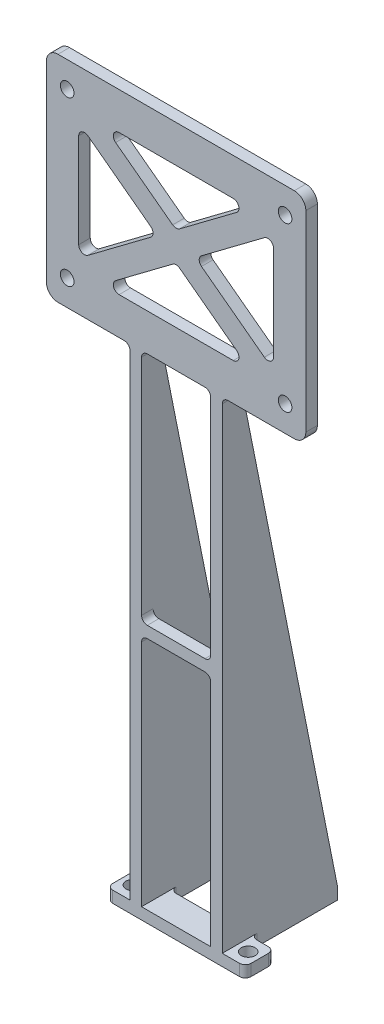
SolidWorks part; units mm, degrees
material "7075-T6 (SN)"
ref_plane "Front Plane" through (0, 0, 0) normal (0, 0, 1) x (1, 0, 0)
ref_plane "Top Plane" through (0, 0, 0) normal (0, 1, 0) x (1, 0, 0)
ref_plane "Right Plane" through (0, 0, 0) normal (1, 0, 0) x (0, 0, -1)
sketch "Sketch1" plane through (0, 0, 0) normal (0, 0, 1) x (-1, 0, 0)
  line L8 (-27.9, -31.869) -> (27.9, -31.869)
  line L9 (31.869, -27.9) -> (31.869, 27.9)
  line L10 (27.9, 31.869) -> (-27.9, 31.869)
  line L11 (-31.869, 27.9) -> (-31.869, -27.9)
  arc A2 (-25.5, 18) -> (-22.5, 18) centre (-24, 18) ccw
  arc A3 (-22.5, 18) -> (-25.5, 18) centre (-24, 18) ccw
  arc A8 (27.9, -31.869) -> (31.869, -27.9) centre (27.9, -27.9) ccw
  arc A9 (31.869, 27.9) -> (27.9, 31.869) centre (27.9, 27.9) ccw
  arc A10 (-27.9, 31.869) -> (-31.869, 27.9) centre (-27.9, 27.9) ccw
  arc A11 (-31.869, -27.9) -> (-27.9, -31.869) centre (-27.9, -27.9) ccw
  arc A14 (22.5, 18) -> (25.5, 18) centre (24, 18) ccw
  arc A15 (25.5, 18) -> (22.5, 18) centre (24, 18) ccw
  arc A18 (25.5, -18) -> (22.5, -18) centre (24, -18) ccw
  arc A19 (22.5, -18) -> (25.5, -18) centre (24, -18) ccw
  arc A22 (-22.5, -18) -> (-25.5, -18) centre (-24, -18) ccw
  arc A23 (-25.5, -18) -> (-22.5, -18) centre (-24, -18) ccw
extrude "Boss-Extrude1" add sketch "Sketch1" along normal blind 2.54
sketch "Sketch2" plane through (0, 0, 2.54) normal (0, 0, 1) x (1, 0, 0)
  line L0 (-24, 18) -> (-24, -18) construction
  line L1 (-24, -18) -> (24, -18) construction
  line L3 (-24, 18) -> (24, 18) construction
  line L4 (24, -18) -> (24, 18) construction
  line L5 (-24, -18) -> (24, 18) construction
  line L6 (-24, 18) -> (24, -18) construction
  line L29 (-16.38, 15.46) -> (0, 3.175)
  line L31 (-13.455, -10.0913) -> (13.455, -10.0913) construction
  line L32 (-13.455, -10.0913) -> (-13.455, 10.0913) construction
  line L33 (-13.455, 10.0913) -> (13.455, 10.0913) construction
  line L34 (13.455, -10.0913) -> (13.455, 10.0913) construction
  line L35 (-13.455, -10.0913) -> (13.455, 10.0913) construction
  line L36 (-13.455, 10.0913) -> (13.455, -10.0913) construction
  line L37 (-16.38, 15.46) -> (16.38, 15.46)
  line L38 (21.46, 12.92) -> (21.46, -12.92)
  line L40 (4.2333, 0) -> (21.46, -12.92)
  line L41 (-21.46, -12.92) -> (-21.46, 12.92)
  line L42 (-22.476, 20.032) -> (25.524, -15.968) construction
  line L43 (4.2333, 0) -> (21.46, 12.92)
  line L45 (0, -3.175) -> (16.38, -15.46)
  line L47 (0, 3.175) -> (16.38, 15.46)
  line L49 (-16.38, -15.46) -> (0, -3.175)
  line L50 (-21.46, -12.92) -> (-4.2333, 0)
  line L53 (16.38, -15.46) -> (-16.38, -15.46)
  line L54 (-21.46, 12.92) -> (-4.2333, 0)
  circle A0 centre (24, 18) radius 2.54 construction
  circle A1 centre (24, -18) radius 2.54 construction
  circle A2 centre (-24, -18) radius 2.54 construction
  circle A3 centre (-24, 18) radius 2.54 construction
  point P0 (0, 0)
  point P27 (0, 0)
  dimension "D4" = 2.54
extrude "Cut-Extrude1" cut sketch "Sketch2" against normal blind 2.54
sketch "Sketch3" plane through (0, 0, 2.54) normal (0, 0, 1) x (1, 0, 0)
  line L0 (0, 15.46) -> (0, 23.6645) construction
  line L1 (16.38, 15.46) -> (-16.38, 15.46) construction
  line L2 (27.9, 31.869) -> (-27.9, 31.869) construction
  line L3 (21.46, 0) -> (31.869, 0) construction
  line L4 (21.46, -12.92) -> (21.46, 12.92) construction
  line L5 (31.869, -27.9) -> (31.869, 27.9) construction
  line L6 (-21.46, 0) -> (-31.869, 0) construction
  line L7 (-21.46, 12.92) -> (-21.46, -12.92) construction
  line L8 (-31.869, 27.9) -> (-31.869, -27.9) construction
  line L9 (0, -15.46) -> (0, -23.6645) construction
  line L10 (-16.38, -15.46) -> (16.38, -15.46) construction
  line L11 (-27.9, -31.869) -> (27.9, -31.869) construction
  line L12 (0, -27.4745) -> (0, -31.869) construction
  line L13 (-20.32, 19.8545) -> (20.32, 19.8545)
  line L14 (-20.32, 19.8545) -> (-20.32, 23.6645)
  line L16 (20.32, 19.8545) -> (20.32, 23.6645)
  line L17 (-20.32, 19.8545) -> (20.32, 27.4745) construction
  line L18 (-20.32, 27.4745) -> (20.32, 19.8545) construction
  line L20 (-20.32, -23.6645) -> (-20.32, -19.8545)
  line L21 (-20.32, -19.8545) -> (20.32, -19.8545)
  line L22 (20.32, -23.6645) -> (20.32, -19.8545)
  line L23 (-20.32, -27.4745) -> (20.32, -19.8545) construction
  line L24 (-20.32, -19.8545) -> (20.32, -27.4745) construction
  line L25 (-24.7595, -13.97) -> (-28.5695, -13.97)
  line L26 (-24.7595, -13.97) -> (-24.7595, 13.97)
  line L27 (-24.7595, 13.97) -> (-28.5695, 13.97)
  line L28 (-28.5695, -13.97) -> (-28.5695, 13.97)
  line L29 (-24.7595, -13.97) -> (-28.5695, 13.97) construction
  line L30 (-24.7595, 13.97) -> (-28.5695, -13.97) construction
  line L31 (24.7595, -13.97) -> (28.5695, -13.97)
  line L32 (24.7595, -13.97) -> (24.7595, 13.97)
  line L33 (24.7595, 13.97) -> (28.5695, 13.97)
  line L34 (28.5695, -13.97) -> (28.5695, 13.97)
  line L35 (24.7595, -13.97) -> (28.5695, 13.97) construction
  line L36 (24.7595, 13.97) -> (28.5695, -13.97) construction
  line L39 (20.32, 23.6645) -> (28.5695, 23.6645)
  line L40 (28.5695, 27.4745) -> (28.5695, 23.6645)
  line L43 (-20.32, 23.6645) -> (-28.5695, 23.6645)
  line L44 (-28.5695, 27.4745) -> (-28.5695, 23.6645)
  line L45 (20.32, -23.6645) -> (28.5695, -23.6645)
  line L48 (28.5695, -23.6645) -> (28.5695, -27.4745)
  line L49 (-20.32, -23.6645) -> (-28.5695, -23.6645)
  line L52 (-28.5695, -23.6645) -> (-28.5695, -27.4745)
  line L53 (0, 27.4745) -> (0, 31.869) construction
  line L54 (-28.5695, 27.4745) -> (28.5695, 27.4745)
  line L55 (-28.5695, -27.4745) -> (28.5695, -27.4745)
  point P24 (0, 23.6645)
  point P29 (0, -23.6645)
  point P34 (-26.6645, 0)
  point P39 (26.6645, 0)
sketch "Sketch4" plane through (0, 0, 2.54) normal (0, 0, 1) x (1, 0, 0)
  line L1 (-28.5695, -23.6645) -> (28.5695, -23.6645)
  line L2 (-28.5695, -23.6645) -> (-28.5695, 23.6645)
  line L3 (-28.5695, 23.6645) -> (28.5695, 23.6645)
  line L4 (28.5695, -23.6645) -> (28.5695, 23.6645)
  line L5 (-28.5695, -23.6645) -> (28.5695, 23.6645) construction
  line L6 (-28.5695, 23.6645) -> (28.5695, -23.6645) construction
  line L10 (27.9, 31.869) -> (-27.9, 31.869)
  line L11 (-31.869, 27.9) -> (-31.869, -27.9)
  line L12 (-27.9, -31.869) -> (27.9, -31.869)
  line L13 (31.869, -27.9) -> (31.869, 27.9)
  line L14 (27.9, 31.869) -> (-27.9, 31.869)
  line L15 (-31.869, 27.9) -> (-31.869, -27.9)
  line L16 (-27.9, -31.869) -> (27.9, -31.869)
  line L17 (31.869, -27.9) -> (31.869, 27.9)
  arc A4 (31.869, 27.9) -> (27.9, 31.869) centre (27.9, 27.9) ccw
  arc A5 (-27.9, 31.869) -> (-31.869, 27.9) centre (-27.9, 27.9) ccw
  arc A6 (-31.869, -27.9) -> (-27.9, -31.869) centre (-27.9, -27.9) ccw
  arc A7 (27.9, -31.869) -> (31.869, -27.9) centre (27.9, -27.9) ccw
  arc A8 (31.869, 27.9) -> (27.9, 31.869) centre (27.9, 27.9) ccw
  arc A9 (-27.9, 31.869) -> (-31.869, 27.9) centre (-27.9, 27.9) ccw
  arc A10 (-31.869, -27.9) -> (-27.9, -31.869) centre (-27.9, -27.9) ccw
  arc A11 (27.9, -31.869) -> (31.869, -27.9) centre (27.9, -27.9) ccw
  point P0 (0, 0)
  dimension "D1" = 0
extrude "Cut-Extrude3" cut sketch "Sketch4" against normal blind 2.54
fillet "Fillet5" radius 1.27 8 edges at (-21.46, 12.92, 1.27) (-21.46, -12.92, 1.27) (-16.38, -15.46, 1.27) (16.38, -15.46, 1.27) (21.46, -12.92, 1.27) (21.46, 12.92, 1.27) (-16.38, 15.46, 1.27) (16.38, 15.46, 1.27)
fillet "Fillet6" radius 1.27 4 edges at (-4.2333, 0, 1.27) (0, -3.175, 1.27) (4.2333, 0, 1.27) (0, 3.175, 1.27)
fillet "Fillet7" radius 2.54 4 edges at (-28.5695, -23.6645, 1.27) (28.5695, -23.6645, 1.27) (28.5695, 23.6645, 1.27) (-28.5695, 23.6645, 1.27)
sketch "Sketch5" plane through (0, 0, 2.54) normal (0, 0, 1) x (1, 0, 0)
  line L2 (-7.8538, -15.46) -> (-7.8538, -129.76)
  line L3 (-7.8538, -129.76) -> (8.0245, -129.76)
  line L4 (8.0245, -15.46) -> (8.0245, -129.76)
  line L5 (0.9561, -15.46) -> (8.0245, -129.76) construction
  line L6 (-7.8538, -129.76) -> (-0.9357, -15.46) construction
  line L7 (-7.8538, -15.46) -> (8.0245, -15.46)
  line L8 (-12.57, -15.46) -> (12.57, -15.46) construction
  point P0 (0, 0)
sketch "Sketch6" plane through (0, 0, 0) normal (1, 0, 0) x (0, 0, -1)
  line L7 (-2.54, -129.76) -> (-2.54, -23.6645)
  line L8 (-2.54, -129.76) -> (-2.54, -15.46) construction
  line L12 (-2.54, -129.76) -> (22.86, -129.76)
  line L16 (-2.54, -15.46) -> (0, -15.46)
  line L17 (0, -15.46) -> (22.86, -129.76)
  line L18 (-2.54, -15.46) -> (-2.54, -23.6645)
extrude "Boss-Extrude2" add sketch "Sketch6" along normal blind 10.16 and the other way blind 10.16
sketch "Sketch7" plane through (0, 0, 2.54) normal (0, 0, 1) x (1, 0, 0)
  line L0 (10.16, -76.7123) -> (-10.16, -76.7123) construction
  line L1 (-10.16, -23.6645) -> (10.16, -23.6645) construction
  line L2 (-10.16, -23.6645) -> (-10.16, -129.76) construction
  line L3 (-10.16, -129.76) -> (10.16, -129.76) construction
  line L4 (10.16, -23.6645) -> (10.16, -129.76) construction
  line L6 (-7.62, -23.6645) -> (7.62, -23.6645)
  line L7 (-7.62, -23.6645) -> (-7.62, -129.76)
  line L8 (-7.62, -129.76) -> (7.62, -129.76)
  line L9 (7.62, -23.6645) -> (7.62, -129.76)
  line L10 (-7.62, -23.6645) -> (7.62, -129.76) construction
  line L11 (-7.62, -129.76) -> (7.62, -23.6645) construction
  point P8 (0, -76.7123)
extrude "Cut-Extrude4" cut sketch "Sketch7" against normal blind 52.324
sketch "Sketch8" plane through (0, -129.76, 0) normal (0, -1, 0) x (1, 0, 0)
  line L0 (27.9, 2.54) -> (-27.9, 2.54) construction
  line L1 (-15.24, -3.81) -> (-10.16, -3.81)
  line L2 (-15.24, -3.81) -> (-15.24, 2.54)
  line L3 (-15.24, 2.54) -> (15.24, 2.54)
  line L4 (15.24, -3.81) -> (15.24, 2.54) construction
  line L5 (-15.24, -3.81) -> (15.24, 2.54) construction
  line L6 (-15.24, 2.54) -> (15.24, -3.81) construction
  line L7 (10.16, 2.54) -> (10.16, -22.86) construction
  line L8 (15.24, 2.54) -> (10.16, 2.54) construction
  line L9 (15.24, 2.54) -> (15.24, -3.81) construction
  line L10 (15.24, -3.81) -> (10.16, -3.81) construction
  line L11 (10.16, 2.54) -> (10.16, -3.81) construction
  line L12 (-10.16, 2.54) -> (-10.16, -22.86) construction
  line L13 (-15.24, 2.54) -> (-10.16, 2.54) construction
  line L14 (-15.24, 2.54) -> (-15.24, -3.81) construction
  line L15 (-15.24, -3.81) -> (-10.16, -3.81) construction
  line L16 (-10.16, 2.54) -> (-10.16, -3.81) construction
  line L17 (10.16, -3.81) -> (15.24, -3.81)
  line L18 (-10.16, -3.81) -> (10.16, -3.81)
  line L19 (-7.62, -22.86) -> (-7.62, 2.54) construction
  line L20 (-15.24, -3.81) -> (15.24, -3.81)
  line L21 (-15.24, -3.81) -> (-15.24, 2.54)
  line L22 (-15.24, 2.54) -> (15.24, 2.54)
  line L23 (15.24, -3.81) -> (15.24, 2.54)
  line L24 (7.62, -22.86) -> (-7.62, -22.86)
  line L25 (7.62, -22.86) -> (7.62, -16.51)
  line L26 (7.62, -16.51) -> (-7.62, -16.51)
  line L27 (-7.62, -22.86) -> (-7.62, -16.51)
  line L28 (-15.24, -0.635) -> (15.24, -0.635) construction
  line L29 (-7.62, -16.51) -> (7.62, -16.51)
  line L30 (-7.62, -16.51) -> (-7.62, -22.86)
  line L31 (-7.62, -22.86) -> (7.62, -22.86)
  line L32 (7.62, -16.51) -> (7.62, -22.86)
  line L33 (-7.62, -16.51) -> (7.62, -22.86) construction
  line L34 (-7.62, -22.86) -> (7.62, -16.51) construction
  line L36 (-10.16, -3.81) -> (-7.62, -3.81)
  line L37 (-10.16, -3.81) -> (-10.16, -22.86)
  line L38 (-10.16, -22.86) -> (-7.62, -22.86)
  line L39 (-7.62, -3.81) -> (-7.62, -22.86)
  line L40 (10.16, -3.81) -> (7.62, -3.81)
  line L41 (10.16, -3.81) -> (10.16, -22.86)
  line L42 (10.16, -22.86) -> (7.62, -22.86)
  line L43 (7.62, -3.81) -> (7.62, -22.86)
  circle A3 centre (0, -19.685) radius 1.524
  circle A4 centre (-12.7, -0.635) radius 1.524
  circle A5 centre (12.7, -0.635) radius 1.524
  point P0 (0, 0)
extrude "Boss-Extrude3" add sketch "Sketch8" along normal blind 2.54
sketch "Sketch10" plane through (0, -23.6645, 0) normal (0, -1, 0) x (1, 0, 0)
  line L1 (-6.3812, 0) -> (7.62, 0)
  line L2 (-6.3812, 0) -> (-6.3812, 2.54)
  line L3 (-6.3812, 2.54) -> (7.62, 2.54)
  line L4 (7.62, 0) -> (7.62, 2.54)
  line L5 (-6.3812, 0) -> (7.62, 0)
  line L6 (-6.3812, 0) -> (-6.3812, -1.6409)
  line L7 (-6.3812, -1.6409) -> (7.62, -1.6409)
  line L8 (7.62, 0) -> (7.62, -1.6409)
  line M1 (-7.62, -1.6409) -> (7.62, -1.6409)
  line M2 (7.62, -1.6409) -> (7.62, 2.54)
  line M4 (-7.62, 2.54) -> (-7.62, -1.6409)
extrude "Cut-Extrude5" cut sketch "Sketch10" against normal blind 12.192 contours L1 M4 M1 M2
fillet "Fillet9" radius 1.27 4 edges at (7.62, -23.6645, 1.27) (-7.62, -23.6645, 0.4495) (-10.16, -23.6645, 1.27) (10.16, -23.6645, 1.27)
fillet "Fillet10" radius 1.27 10 edges at (7.62, -131.03, -3.81) (7.62, -131.03, -16.51) (-7.62, -131.03, -16.51) (10.16, -131.03, -3.81) (15.24, -131.03, -3.81) (15.24, -131.03, 2.54) (-15.24, -131.03, 2.54) (-15.24, -131.03, -3.81) (-7.62, -131.03, -3.81) (-10.16, -131.03, -3.81)
sketch "Sketch11" plane through (0, 0, 2.54) normal (0, 0, 1) x (1, 0, 0)
  line L0 (-28.5695, -23.6645) -> (28.5695, -23.6645) construction
  line L1 (7.62, -129.76) -> (-7.6769, -129.76) construction
  line L2 (7.62, -129.76) -> (7.62, -23.6645) construction
  line L3 (7.62, -23.6645) -> (-7.6769, -23.6645) construction
  line L4 (-7.6769, -129.76) -> (-7.6769, -23.6645) construction
  line L6 (-7.6769, -23.6645) -> (7.62, -23.6645) construction
  line L7 (-7.6769, -23.6645) -> (-7.6769, -129.76) construction
  line L8 (-7.6769, -129.76) -> (7.62, -129.76) construction
  line L9 (7.62, -23.6645) -> (7.62, -129.76) construction
  line L10 (-7.6769, -23.6645) -> (7.62, -129.76) construction
  line L11 (-7.6769, -129.76) -> (7.62, -23.6645) construction
  line L12 (-7.6769, -77.9823) -> (7.62, -77.9823)
  line L13 (-7.6769, -77.9823) -> (-7.6769, -75.4423)
  line L14 (-7.6769, -75.4423) -> (7.62, -75.4423)
  line L15 (7.62, -77.9823) -> (7.62, -75.4423)
  line L16 (-7.6769, -77.9823) -> (7.62, -75.4423) construction
  line L17 (-7.6769, -75.4423) -> (7.62, -77.9823) construction
  point P7 (-0.0284, -76.7123)
  point P8 (-0.0284, -76.7123)
extrude "Boss-Extrude4" add sketch "Sketch11" against normal blind 2.54
fillet "Fillet12" radius 1.27 4 edges at (7.62, -77.9823, 1.27) (-7.62, -77.9823, 1.27) (-7.62, -75.4423, 1.27) (7.62, -75.4423, 1.27)
